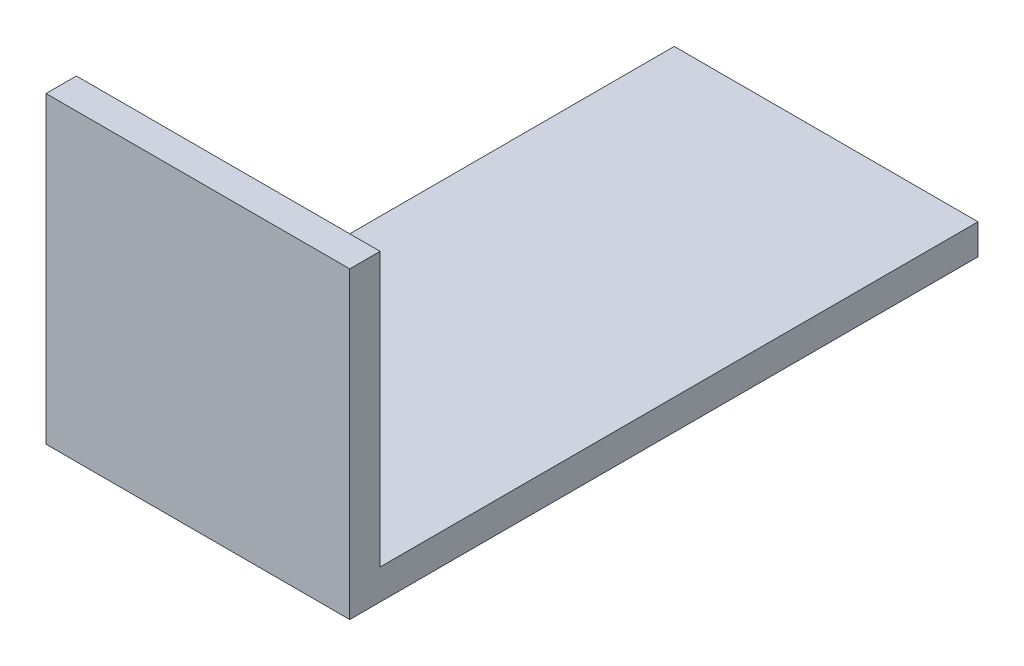
SolidWorks part; units mm, degrees
ref_plane "Front Plane" through (0, 0, 0) normal (0, 0, 1) x (1, 0, 0)
ref_plane "Top Plane" through (0, 0, 0) normal (0, 1, 0) x (1, 0, 0)
ref_plane "Right Plane" through (0, 0, 0) normal (1, 0, 0) x (0, 0, -1)
sketch "Sketch1" plane through (0, 0, 0) normal (1, 0, 0) x (0, 0, -1)
  line L0 (0, -12.7) -> (0, 0) construction
  line L1 (0, 0) -> (250, 0)
  line L3 (0, -12.7) -> (250, -12.7)
  line L4 (250, 0) -> (250, -12.7)
  line L5 (0, -12.7) -> (-12.7, -12.7)
  line L6 (0, 0) -> (0, 114.3)
  line L7 (0, 114.3) -> (-12.7, 114.3)
  line L8 (-12.7, -12.7) -> (-12.7, 114.3)
  dimension "D1" = 12.7
  dimension "D2" = 250
  dimension "D3" = 127
extrude "Boss-Extrude1" add sketch "Sketch1" along normal mid plane 127
